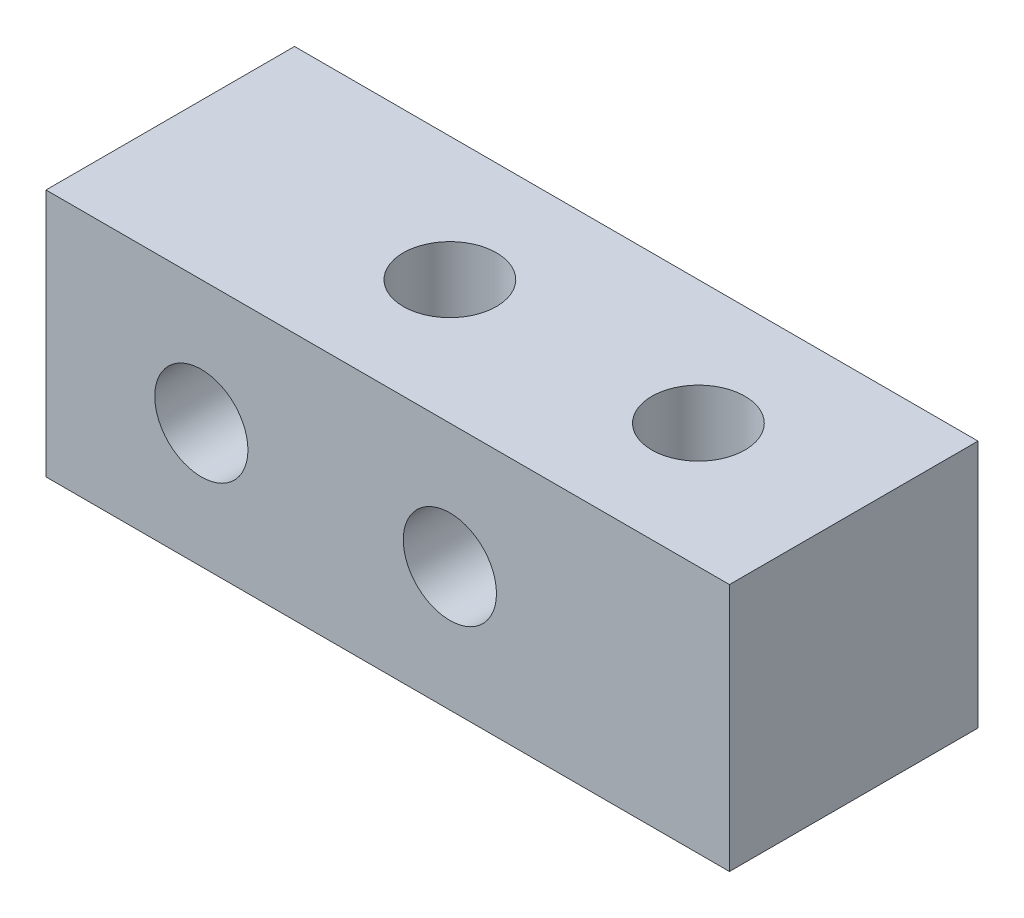
SolidWorks part; units mm, degrees
ref_plane "Front Plane" through (0, 0, 0) normal (0, 0, 1) x (1, 0, 0)
ref_plane "Top Plane" through (0, 0, 0) normal (0, 1, 0) x (1, 0, 0)
ref_plane "Right Plane" through (0, 0, 0) normal (1, 0, 0) x (0, 0, -1)
other "Configuration Table"
sketch "草图1" plane through (0, 0, 0) normal (0, 1, 0) x (1, 0, 0)
  line L1 (0, 0) -> (22, 0)
  line L2 (0, 0) -> (0, -8)
  line L3 (0, -8) -> (22, -8)
  line L4 (22, 0) -> (22, -8)
  dimension "D1" = 22
  dimension "D2" = 8
extrude "凸台-拉伸1" add sketch "草图1" along normal blind 8
sketch "草图2" plane through (0, 8, 0) normal (0, 1, 0) x (1, 0, 0)
  line L0 (22, -8) -> (22, 0) construction
  line L1 (22, -4) -> (5.427, -4) construction
  circle A0 centre (17, -4) radius 1.5
  circle A1 centre (9, -4) radius 1.5
  point P6 (22, -4)
  point P9 (0, 0)
  point P10 (0, 0)
  dimension "D1" = 3
  dimension "D2" = 3
  dimension "D3" = 8
  dimension "D4" = 5
extrude "切除-拉伸1" cut sketch "草图2" against normal blind 8
sketch "草图3" plane through (0, 0, 8) normal (0, 0, 1) x (1, 0, 0)
  line L0 (0, 4) -> (17.2522, 4) construction
  line L1 (0, 8) -> (0, 0) construction
  circle A0 centre (5, 4) radius 1.5
  circle A1 centre (13, 4) radius 1.5
  point P8 (0, 0)
  point P9 (0, 0)
  dimension "D1" = 3
  dimension "D2" = 8
  dimension "D3" = 5
extrude "切除-拉伸2" cut sketch "草图3" against normal blind 8
